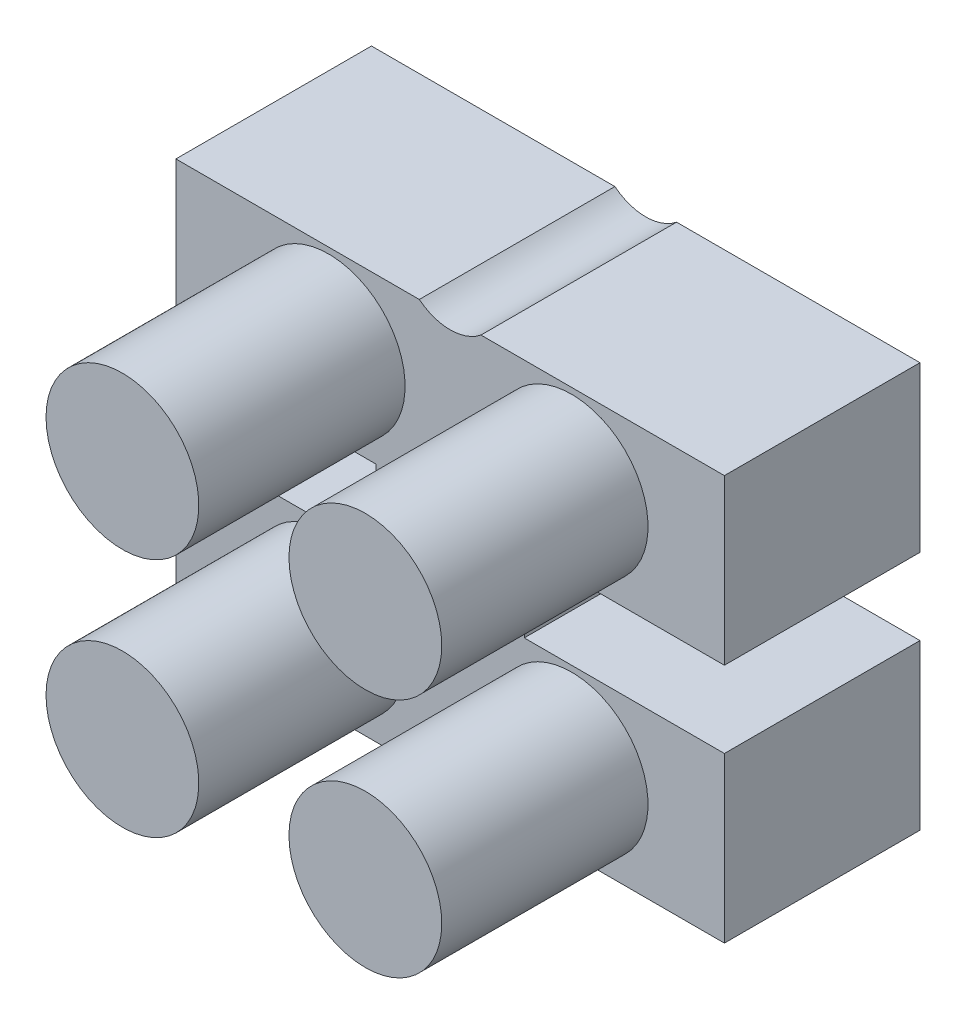
SolidWorks part; units mm, degrees
material "Nylon 6/10"
ref_plane "Front Plane" through (0, 0, 0) normal (0, 0, 1) x (1, 0, 0)
ref_plane "Top Plane" through (0, 0, 0) normal (0, 1, 0) x (1, 0, 0)
ref_plane "Right Plane" through (0, 0, 0) normal (1, 0, 0) x (0, 0, -1)
sketch "Sketch1" plane through (0, 0, 0) normal (0, 0, 1) x (1, 0, 0)
  line L1 (-9.1186, -6.7437) -> (9.1186, -6.7437)
  line L2 (-9.1186, -6.7437) -> (-9.1186, 6.7437)
  line L3 (-9.1186, 6.7437) -> (9.1186, 6.7437)
  line L4 (9.1186, -6.7437) -> (9.1186, 6.7437)
  line L5 (-9.1186, -6.7437) -> (9.1186, 6.7437) construction
  line L6 (-9.1186, 6.7437) -> (9.1186, -6.7437) construction
  point P0 (0, 0)
  dimension "D1" = 13.4874
  dimension "D2" = 18.2372
extrude "Boss-Extrude1" add sketch "Sketch1" along normal blind 6.5024
sketch "Sketch2" plane through (0, 0, 6.5024) normal (0, 0, 1) x (1, 0, 0)
  line L0 (9.1186, -6.7437) -> (9.1186, 6.7437) construction
  line L1 (9.1186, 1.27) -> (2.4638, 1.27)
  line L2 (9.1186, 1.27) -> (9.1186, -1.27)
  line L3 (9.1186, -1.27) -> (2.4638, -1.27)
  line L4 (2.4638, 1.27) -> (2.4638, -1.27)
  line L5 (2.4638, 0) -> (0, 0) construction
  dimension "D1" = 2.54
  dimension "D2" = 6.6548
extrude "Cut-Extrude1" cut sketch "Sketch2" against normal through all
sketch "Sketch5" plane through (0, 0, 6.5024) normal (0, 0, 1) x (1, 0, 0)
  line L0 (4.0386, -4.0069) -> (9.1186, -4.0068) construction
  line L2 (9.1186, -6.7437) -> (9.1186, -1.27) construction
  circle A0 centre (4.0386, -4.0069) radius 2.54
  dimension "D1" = 5.08
  dimension "D2" = 5.08
extrude "Boss-Extrude2" add sketch "Sketch5" along normal blind 6.858
sketch "Sketch6" plane through (0, 0, 6.5024) normal (0, 0, 1) x (1, 0, 0)
  line L1 (9.1186, 1.27) -> (-9.1186, 1.27)
  line L2 (9.1186, 1.27) -> (9.1186, 6.7437)
  line L3 (9.1186, 6.7437) -> (-9.1186, 6.7437)
  line L4 (-9.1186, 1.27) -> (-9.1186, 6.7437)
extrude "Cut-Extrude2" cut sketch "Sketch6" against normal through all
hole_wizard "#4 Clearance Hole1" positions "Sketch4" profile "Sketch3" hole size "#4" standard "ANSI Inch" end condition through all
sketch "Sketch4" plane through (0, 0, 6.5024) normal (0, 0, 1) x (1, 0, 0)
  point P0 (0, 0)
sketch "Sketch3" plane through (0, 0, 6.5024) normal (1, 0, 0) x (0, -1, 0)
  line L0 (0, 0) -> (0, 6.5024)
  line L1 (0, 6.5024) -> (1.6319, 6.5024)
  line L2 (1.6319, 6.5024) -> (1.6319, 0)
  line L5 (1.6319, 0) -> (0, 0)
  line L11 (0, -6.35) -> (0, 107.95) construction
  dimension "Thru Hole Dia." = 3.2639
  dimension "Thru Hole Depth" = 6.5024
mirror "Mirror4" about plane through (0, 0, 0) normal (1, 0, 0) of "Cut-Extrude1", "Boss-Extrude2"
pattern_linear "LPattern1" count 4 spacing 8.001 along (0, 1, 0) of "Boss-Extrude1", "Cut-Extrude1", "#4 Clearance Hole1", "Boss-Extrude2", "Mirror4"
sketch "Sketch7" plane through (0, 0, 6.5024) normal (0, 0, 1) x (1, 0, 0)
  line L1 (-9.1186, 30.7467) -> (9.1186, 30.7467)
  line L2 (-9.1186, 30.7467) -> (-9.1186, 22.733)
  line L3 (-9.1186, 22.733) -> (9.1186, 22.733)
  line L4 (9.1186, 30.7467) -> (9.1186, 22.733)
extrude "Cut-Extrude3" cut sketch "Sketch7" against normal through all
sketch "Sketch8" plane through (0, 0, 0) normal (0, 0, 1) x (1, 0, 0)
  line L1 (-9.1186, 9.271) -> (9.1186, 9.271)
  line L2 (-9.1186, 9.271) -> (-9.1186, -6.7437)
  line L3 (-9.1186, -6.7437) -> (9.1186, -6.7437)
  line L4 (9.1186, 9.271) -> (9.1186, -6.7437)
extrude "Cut-Extrude5" cut sketch "Sketch8" along normal through all
